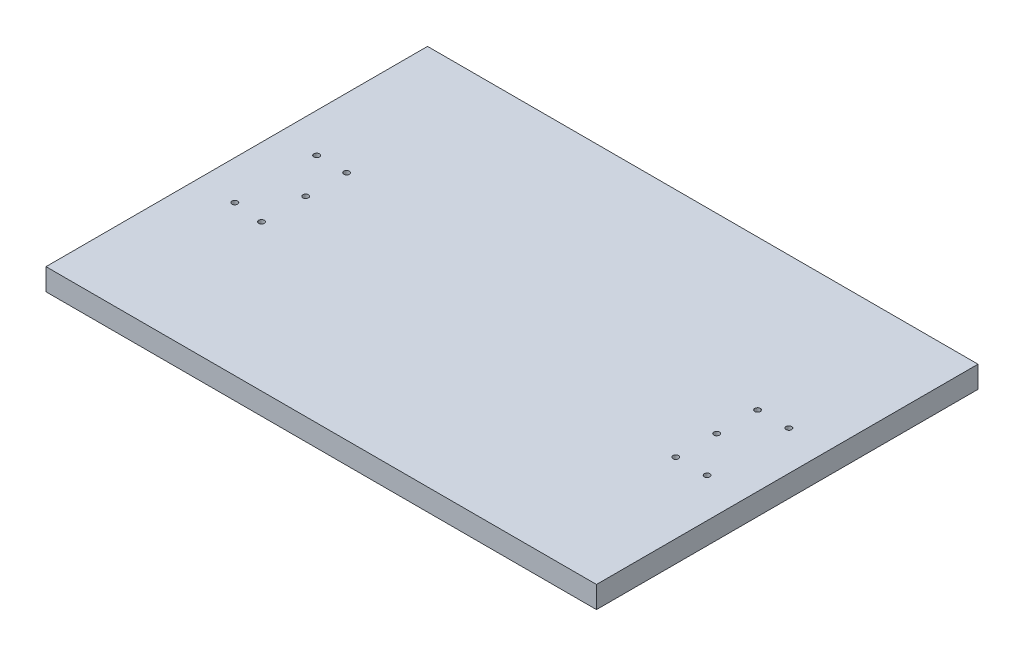
SolidWorks part; units mm, degrees
material "Plain Carbon Steel"
ref_plane "Front Plane" through (0, 0, 0) normal (0, 0, 1) x (1, 0, 0)
ref_plane "Top Plane" through (0, 0, 0) normal (0, 1, 0) x (1, 0, 0)
ref_plane "Right Plane" through (0, 0, 0) normal (1, 0, 0) x (0, 0, -1)
sketch "Sketch1" plane through (0, 0, 0) normal (1, 0, 0) x (0, 0, -1)
  line L1 (-350, -20) -> (350, -20)
  line L2 (-350, -20) -> (-350, 20)
  line L3 (-350, 20) -> (350, 20)
  line L4 (350, -20) -> (350, 20)
  line L5 (-350, -20) -> (350, 20) construction
  line L6 (-350, 20) -> (350, -20) construction
  point P0 (0, 0)
  dimension "D1" = 700
  dimension "D2" = 40
extrude "Boss-Extrude1" add sketch "Sketch1" along normal mid plane 1010
hole_wizard "M12 Tapped Hole1" positions "Sketch4" profile "Sketch3" tap size "M12" standard "ISO"
sketch "Sketch4" plane through (0, 20, 0) normal (0, 1, 0) x (1, 0, 0)
  point P0 (-378.5, 75.052)
  point P3 (-433.5, 75)
  point P6 (-378.5, -81.131)
  point P9 (-433.5, -75)
  point P12 (433, 75)
  point P15 (375.5, 75)
  point P18 (433, -75)
  point P21 (375.5, -75)
  point P24 (375.5, 0)
  point P27 (-378.5, 0)
sketch "Sketch3" plane through (-378.5, 20, -75.052) normal (1, 0, 0) x (0, 0, 1)
  line L0 (0, 0) -> (0, 32.3144)
  line L1 (0, 32.3144) -> (5.1, 29.25)
  line L2 (5.1, 29.25) -> (5.1, 0)
  line L5 (5.1, 0) -> (0, 0)
  line L10 (0, 32.3144) -> (-5.1, 29.25) construction
  line L11 (0, -6.35) -> (0, 107.95) construction
  dimension "Tap Drill Dia." = 10.2
  dimension "Tap Drill Depth" = 29.25
  dimension "Drill Angle" = 118
cosmetic thread "Hole Thread1"
cosmetic thread "Hole Thread2"
cosmetic thread "Hole Thread3"
cosmetic thread "Hole Thread4"
cosmetic thread "Hole Thread5"
cosmetic thread "Hole Thread6"
cosmetic thread "Hole Thread7"
cosmetic thread "Hole Thread8"
cosmetic thread "Hole Thread9"
cosmetic thread "Hole Thread10"
